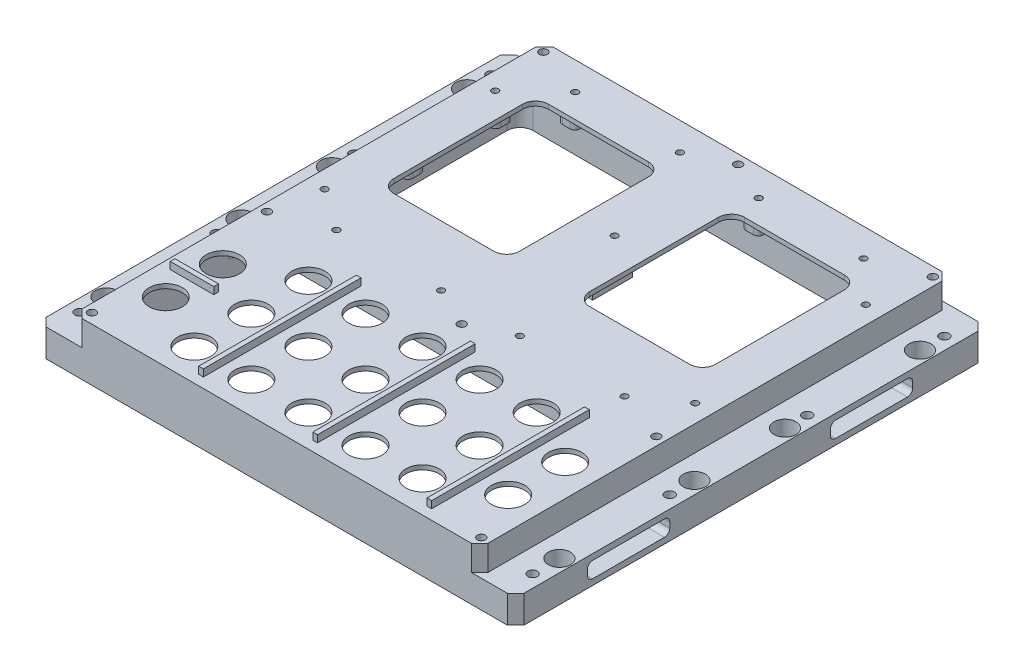
SolidWorks part; units mm, degrees
ref_plane "Front Plane" through (0, 0, 0) normal (0, 0, 1) x (1, 0, 0)
ref_plane "Top Plane" through (0, 0, 0) normal (0, 1, 0) x (1, 0, 0)
ref_plane "Right Plane" through (0, 0, 0) normal (1, 0, 0) x (0, 0, -1)
sketch "Sketch1" plane through (0, 0, 0) normal (0, 1, 0) x (1, 0, 0)
  line L0 (0, 199.644) -> (3.556, 203.2)
  line L1 (3.556, 0) -> (202.7936, 0)
  line L2 (0, 3.556) -> (0, 199.644)
  line L3 (3.556, 203.2) -> (202.7936, 203.2)
  line L4 (206.3496, 3.556) -> (206.3496, 199.644)
  line L5 (202.7936, 203.2) -> (206.3496, 199.644)
  line L6 (202.7936, 0) -> (206.3496, 3.556)
  line L7 (0, 3.556) -> (3.556, 0)
  point P0 (0, 0)
  point P1 (206.3496, 203.2)
  point P2 (0, 203.2)
  point P3 (206.3496, 0)
  dimension "D1" = 203.2
  dimension "D2" = 206.3496
  dimension "D3" = 3.556
  dimension "D4" = 45
  dimension "D5" = 3.556
  dimension "D6" = 45
  dimension "D7" = 3.556
  dimension "D8" = 45
  dimension "D9" = 3.556
  dimension "D10" = 45
extrude "Boss-Extrude1" add sketch "Sketch1" along normal blind 22.8727
sketch "Sketch3" plane through (0, 0, -203.2) normal (0, 0, -1) x (-1, 0, 0)
  line L0 (-190.8048, 11.9507) -> (-15.5448, 11.9507) construction
  line L1 (-206.3496, 22.8727) -> (-190.8048, 22.8727)
  line L2 (-206.3496, 22.8727) -> (-206.3496, 11.9507)
  line L3 (-206.3496, 11.9507) -> (-190.8048, 11.9507)
  line L4 (-190.8048, 22.8727) -> (-190.8048, 11.9507)
  line L5 (0, 22.8727) -> (-15.5448, 22.8727)
  line L6 (0, 22.8727) -> (0, 11.9507)
  line L7 (0, 11.9507) -> (-15.5448, 11.9507)
  line L8 (-15.5448, 22.8727) -> (-15.5448, 11.9507)
  line L9 (-202.7936, 22.8727) -> (-3.556, 22.8727) construction
  point P10 (-103.1748, 11.9507)
  point P13 (-103.1748, 22.8727)
  dimension "D1" = 10.922
  dimension "D2" = 175.26
extrude "Cut-Extrude1" cut sketch "Sketch3" against normal through all
chamfer "Chamfer1" distance 3.556 angle 45 4 edges at (190.8048, 17.4117, 0) (15.5448, 17.4117, 0) (15.5448, 17.4117, -203.2) (190.8048, 17.4117, -203.2)
sketch "Sketch4" plane through (0, 22.8727, 0) normal (0, 1, 0) x (1, 0, 0)
  line L0 (-41.9282, 73.533) -> (82.8548, 73.533)
  line L1 (190.8048, 3.556) -> (190.8048, 199.644) construction
  line L2 (19.1008, 0) -> (187.2488, 0) construction
  line L3 (39.6748, 180.848) -> (82.8548, 180.848)
  line L4 (34.0868, 175.26) -> (34.0868, 119.634)
  line L5 (39.6748, 114.046) -> (82.8548, 114.046)
  line L6 (88.4428, 175.26) -> (88.4428, 119.634)
  line L7 (124.2568, 180.848) -> (167.4368, 180.848)
  line L8 (118.6688, 175.26) -> (118.6688, 119.634)
  line L9 (124.2568, 114.046) -> (167.4368, 114.046)
  line L10 (173.0248, 175.26) -> (173.0248, 119.634)
  line L12 (187.2234, 11.7526) -> (187.2234, -12.2812) construction
  arc A0 (124.2568, 180.848) -> (118.6688, 175.26) centre (124.2568, 175.26) ccw
  arc A1 (167.4368, 180.848) -> (173.0248, 175.26) centre (167.4368, 175.26) cw
  arc A2 (167.4368, 114.046) -> (173.0248, 119.634) centre (167.4368, 119.634) ccw
  arc A3 (118.6688, 119.634) -> (124.2568, 114.046) centre (124.2568, 119.634) ccw
  arc A4 (82.8548, 114.046) -> (88.4428, 119.634) centre (82.8548, 119.634) ccw
  arc A5 (34.0868, 119.634) -> (39.6748, 114.046) centre (39.6748, 119.634) ccw
  arc A6 (39.6748, 180.848) -> (34.0868, 175.26) centre (39.6748, 175.26) ccw
  arc A7 (82.8548, 180.848) -> (88.4428, 175.26) centre (82.8548, 175.26) cw
  circle A8 centre (29.2354, 26.035) radius 7.1819
  circle A9 centre (177.0634, 26.035) radius 7.1819
  circle A10 centre (177.0634, 50.673) radius 7.1819
  circle A11 centre (29.2354, 50.673) radius 7.1819
  circle A12 centre (53.8734, 62.992) radius 7.1819
  circle A13 centre (53.8734, 38.354) radius 7.1819
  circle A14 centre (53.8734, 13.716) radius 7.1819
  circle A15 centre (78.5114, 13.716) radius 7.1819
  circle A16 centre (78.5114, 38.354) radius 7.1819
  circle A17 centre (78.5114, 62.992) radius 7.1819
  circle A18 centre (103.1494, 62.992) radius 7.1819
  circle A19 centre (127.7874, 62.992) radius 7.1819
  circle A20 centre (152.4254, 62.992) radius 7.1819
  circle A21 centre (103.1494, 38.354) radius 7.1819
  circle A22 centre (127.7874, 38.354) radius 7.1819
  circle A23 centre (152.4254, 38.354) radius 7.1819
  circle A24 centre (103.1494, 13.716) radius 7.1819
  circle A25 centre (127.7874, 13.716) radius 7.1819
  circle A26 centre (152.4254, 13.716) radius 7.1819
  point P26 (34.0868, 114.046)
  point P29 (34.0868, 180.848)
  point P32 (88.4428, 180.848)
  dimension "D5" = 5.588
  dimension "D6" = 5.588
  dimension "D9" = 14.3637
  dimension "D12" = 59.436
  dimension "D1" = 3.5814
  dimension "D2" = 66.802
  dimension "D3" = 54.356
  dimension "D4" = 180.848
  dimension "D7" = 17.78
  dimension "D8" = 102.362
  dimension "D10" = 10.16
  dimension "D11" = 34.798
  dimension "D13" = 84.074
  dimension "D14" = 108.712
  dimension "D15" = 133.35
  dimension "D16" = 157.988
  dimension "D17" = 73.533
  dimension "D18" = 10.541
  dimension "D19" = 35.179
  dimension "D20" = 59.817
  dimension "D21" = 22.86
  dimension "D22" = 47.498
extrude "Cut-Extrude2" cut sketch "Sketch4" against normal through all contours A7 L3 A6 L4 A5 L5 A4 L6 | L8 A3 L9 A2 L10 A1 L7 A0 | A19 | A18 | A13 | A14 | A17 | A12 | A11 | A8 | A16 | A21 | A22 | A20 | A10 | A9 | A23 | A26 | A25 | A24 | A15
sketch "Sketch5" plane through (0, 22.8727, 0) normal (0, 1, 0) x (1, 0, 0)
  line L0 (190.8048, 3.556) -> (190.8048, 199.644) construction
  line L1 (19.8628, 39.37) -> (38.6588, 39.37)
  line L2 (19.8628, 39.37) -> (19.8628, 37.338)
  line L3 (19.8628, 37.338) -> (38.6588, 37.338)
  line L4 (38.6588, 39.37) -> (38.6588, 37.338)
  line L5 (65.1764, 72.39) -> (67.2084, 72.39)
  line L6 (65.1764, 72.39) -> (65.1764, 4.318)
  line L7 (65.1764, 4.318) -> (67.2084, 4.318)
  line L8 (67.2084, 72.39) -> (67.2084, 4.318)
  line L9 (114.4524, 72.39) -> (116.4844, 72.39)
  line L10 (114.4524, 72.39) -> (114.4524, 4.318)
  line L11 (114.4524, 4.318) -> (116.4844, 4.318)
  line L12 (116.4844, 72.39) -> (116.4844, 4.318)
  line L13 (165.7604, 72.39) -> (163.7284, 72.39)
  line L14 (165.7604, 72.39) -> (165.7604, 4.318)
  line L15 (165.7604, 4.318) -> (163.7284, 4.318)
  line L16 (163.7284, 72.39) -> (163.7284, 4.318)
  line L17 (19.1008, 0) -> (187.2488, 0) construction
  circle A0 centre (53.8734, 13.716) radius 7.1819 construction
  circle A1 centre (78.5114, 13.716) radius 7.1819 construction
  circle A2 centre (103.1494, 13.716) radius 7.1819 construction
  circle A4 centre (152.4254, 13.716) radius 7.1819 construction
  circle A5 centre (29.2354, 50.673) radius 7.1819 construction
  circle A6 centre (29.2354, 26.035) radius 7.1819 construction
  dimension "D1" = 11.303
  dimension "D2" = 11.303
  dimension "D4" = 11.303
  dimension "D6" = 11.303
  dimension "D3" = 11.303
  dimension "D5" = 68.072
  dimension "D7" = 11.303
  dimension "D8" = 152.146
  dimension "D9" = 18.796
  dimension "D10" = 4.318
extrude "Boss-Extrude2" add sketch "Sketch5" along normal blind 3.048
sketch "Sketch6" plane through (0, 0, -203.2) normal (0, 0, -1) x (-1, 0, 0)
  line L0 (-133.7056, 20.3327) -> (-109.5756, 20.3327)
  line L1 (-174.5996, 20.3327) -> (-146.4056, 20.3327)
  line L2 (-176.8856, 18.0467) -> (-176.8856, 4.826)
  line L3 (-174.5996, 2.54) -> (-146.4056, 2.54)
  line L4 (-144.1196, 18.0467) -> (-144.1196, 4.826)
  line L5 (-96.8756, 20.3327) -> (-72.7456, 20.3327)
  line L6 (-99.1616, 18.0467) -> (-99.1616, 4.826)
  line L7 (-96.8756, 2.54) -> (-72.7456, 2.54)
  line L8 (-70.4596, 18.0467) -> (-70.4596, 4.826)
  line L9 (-59.7916, 20.3327) -> (-31.5976, 20.3327)
  line L10 (-62.0776, 18.0467) -> (-62.0776, 4.826)
  line L11 (-59.7916, 2.54) -> (-31.5976, 2.54)
  line L12 (-29.3116, 18.0467) -> (-29.3116, 4.826)
  line L13 (-135.9916, 18.0467) -> (-135.9916, 4.826)
  line L14 (-133.7056, 2.54) -> (-109.5756, 2.54)
  line L15 (-107.2896, 18.0467) -> (-107.2896, 4.826)
  line L16 (-206.3496, 11.9507) -> (-206.3496, 0) construction
  line L17 (-187.2488, 22.8727) -> (-19.1008, 22.8727) construction
  line L18 (-202.7936, 0) -> (-3.556, 0) construction
  arc A0 (-31.5976, 2.54) -> (-29.3116, 4.826) centre (-31.5976, 4.826) ccw
  arc A1 (-31.5976, 20.3327) -> (-29.3116, 18.0467) centre (-31.5976, 18.0467) cw
  arc A2 (-59.7916, 20.3327) -> (-62.0776, 18.0467) centre (-59.7916, 18.0467) ccw
  arc A3 (-62.0776, 4.826) -> (-59.7916, 2.54) centre (-59.7916, 4.826) ccw
  arc A4 (-72.7456, 2.54) -> (-70.4596, 4.826) centre (-72.7456, 4.826) ccw
  arc A5 (-72.7456, 20.3327) -> (-70.4596, 18.0467) centre (-72.7456, 18.0467) cw
  arc A6 (-99.1616, 4.826) -> (-96.8756, 2.54) centre (-96.8756, 4.826) ccw
  arc A7 (-96.8756, 20.3327) -> (-99.1616, 18.0467) centre (-96.8756, 18.0467) ccw
  arc A8 (-146.4056, 20.3327) -> (-144.1196, 18.0467) centre (-146.4056, 18.0467) cw
  arc A9 (-146.4056, 2.54) -> (-144.1196, 4.826) centre (-146.4056, 4.826) ccw
  arc A10 (-176.8856, 4.826) -> (-174.5996, 2.54) centre (-174.5996, 4.826) ccw
  arc A11 (-174.5996, 20.3327) -> (-176.8856, 18.0467) centre (-174.5996, 18.0467) ccw
  arc A12 (-109.5756, 2.54) -> (-107.2896, 4.826) centre (-109.5756, 4.826) ccw
  arc A13 (-109.5756, 20.3327) -> (-107.2896, 18.0467) centre (-109.5756, 18.0467) cw
  arc A14 (-135.9916, 4.826) -> (-133.7056, 2.54) centre (-133.7056, 4.826) ccw
  arc A15 (-133.7056, 20.3327) -> (-135.9916, 18.0467) centre (-133.7056, 18.0467) ccw
  dimension "D1" = 2.286
  dimension "D10" = 2.286
  dimension "D2" = 32.766
  dimension "D3" = 28.702
  dimension "D4" = 29.464
  dimension "D5" = 70.358
  dimension "D6" = 2.54
  dimension "D7" = 2.54
  dimension "D8" = 107.188
  dimension "D9" = 144.272
extrude "Cut-Extrude3" cut sketch "Sketch6" against normal blind 7.874
fillet "Fillet1" radius 2.286 32 edges at (61.408, 3.2096, -195.326) (62.0776, 11.4363, -195.326) (61.408, 19.6631, -195.326) (45.6946, 20.3327, -195.326) (29.9812, 19.6631, -195.326) (29.3116, 11.4364, -195.326) (29.9812, 3.2096, -195.326) (98.492, 3.2096, -195.326) (99.1616, 11.4363, -195.326) (98.492, 19.6631, -195.326) (84.8106, 20.3327, -195.326) (71.1292, 19.6631, -195.326) (70.4596, 11.4364, -195.326) (71.1292, 3.2096, -195.326) (135.322, 3.2096, -195.326) (135.9916, 11.4363, -195.326) (135.322, 19.6631, -195.326) (121.6406, 20.3327, -195.326) (107.9592, 19.6631, -195.326) (107.2896, 11.4363, -195.326) (107.9592, 3.2096, -195.326) (176.216, 3.2096, -195.326) (176.8856, 11.4363, -195.326) (176.216, 19.6631, -195.326) (160.5026, 20.3327, -195.326) (144.7892, 19.6631, -195.326) (144.1196, 11.4363, -195.326) (144.7892, 3.2096, -195.326) (45.6946, 2.54, -195.326) (84.8106, 2.54, -195.326) (121.6406, 2.54, -195.326) (160.5026, 2.54, -195.326)
sketch "Sketch7" plane through (206.3496, 0, 0) normal (1, 0, 0) x (0, 0, -1)
  line L0 (3.556, 11.9507) -> (199.644, 11.9507) construction
  line L1 (33.274, 2.54) -> (64.262, 2.54)
  line L2 (30.988, 4.826) -> (30.988, 7.1247)
  line L3 (33.274, 9.4107) -> (64.262, 9.4107)
  line L4 (66.548, 4.826) -> (66.548, 7.1247)
  line L5 (138.176, 2.54) -> (169.164, 2.54)
  line L6 (135.89, 4.826) -> (135.89, 7.1247)
  line L7 (138.176, 9.4107) -> (169.164, 9.4107)
  line L8 (171.45, 4.826) -> (171.45, 7.1247)
  line L9 (3.556, 0) -> (199.644, 0) construction
  arc A0 (169.164, 2.54) -> (171.45, 4.826) centre (169.164, 4.826) ccw
  arc A1 (169.164, 9.4107) -> (171.45, 7.1247) centre (169.164, 7.1247) cw
  arc A2 (138.176, 2.54) -> (135.89, 4.826) centre (138.176, 4.826) cw
  arc A3 (135.89, 7.1247) -> (138.176, 9.4107) centre (138.176, 7.1247) cw
  arc A4 (64.262, 2.54) -> (66.548, 4.826) centre (64.262, 4.826) ccw
  arc A5 (64.262, 9.4107) -> (66.548, 7.1247) centre (64.262, 7.1247) cw
  arc A6 (30.988, 7.1247) -> (33.274, 9.4107) centre (33.274, 7.1247) cw
  arc A7 (33.274, 2.54) -> (30.988, 4.826) centre (33.274, 4.826) cw
  dimension "D1" = 2.286
  dimension "D2" = 35.56
  dimension "D3" = 2.54
  dimension "D4" = 2.54
  dimension "D5" = 30.988
  dimension "D6" = 135.89
extrude "Cut-Extrude4" cut sketch "Sketch7" against normal blind 12.7
ref_plane "Plane1" through (103.1748, 0, 0) normal (1, 0, 0) x (0, 0, -1)
mirror "Mirror1" about plane through (103.1748, 0, 0) normal (1, 0, 0) of "Cut-Extrude4"
sketch "Sketch8" plane through (0, 0, 0) normal (0, -1, 0) x (1, 0, 0)
  line L0 (39.37, -2.54) -> (50.4656, -2.54)
  line L3 (188.5696, -18.6857) -> (188.5696, -64.6263)
  line L10 (178.5916, -74.676) -> (27.758, -74.676)
  line L13 (17.78, -64.6263) -> (17.78, -18.6857)
  line L16 (3.556, 0) -> (202.7936, 0) construction
  line L17 (206.3496, -3.556) -> (206.3496, -199.644) construction
  line L19 (141.7846, -8.89) -> (138.4282, -8.89)
  line L22 (64.5142, -8.89) -> (67.8706, -8.89)
  line L24 (81.9192, -2.54) -> (99.7416, -2.54)
  line L25 (155.8332, -2.54) -> (166.9796, -2.54)
  line L26 (106.5572, -2.54) -> (124.3796, -2.54)
  arc A0 (188.5696, -64.6263) -> (184.0865, -70.104) centre (182.9816, -64.6263) cw
  arc A1 (184.0865, -70.104) -> (178.5916, -74.676) centre (178.5916, -69.088) cw
  arc A2 (27.758, -74.676) -> (22.2631, -70.104) centre (27.758, -69.088) cw
  arc A3 (22.2631, -70.104) -> (17.78, -64.6263) centre (23.368, -64.6263) cw
  arc A4 (184.0865, -13.208) -> (188.5696, -18.6857) centre (182.9816, -18.6857) cw
  arc A5 (17.78, -18.6857) -> (22.2631, -13.208) centre (23.368, -18.6857) cw
  arc A6 (184.0865, -13.208) -> (166.9796, -2.54) centre (166.9796, -21.59) ccw
  arc A8 (39.37, -2.54) -> (22.2631, -13.208) centre (39.37, -21.59) ccw
  arc A9 (50.4656, -2.54) -> (64.5142, -8.89) centre (53.8734, -13.716) cw
  circle A10 centre (53.8734, -13.716) radius 7.1819 construction
  arc A11 (81.9192, -2.54) -> (67.8706, -8.89) centre (78.5114, -13.716) ccw
  arc A12 (106.5572, -2.54) -> (99.7416, -2.54) centre (103.1494, -13.716) ccw
  arc A13 (138.4282, -8.89) -> (124.3796, -2.54) centre (127.7874, -13.716) ccw
  arc A14 (141.7846, -8.89) -> (155.8332, -2.54) centre (152.4254, -13.716) cw
  point P18 (0, 0)
  point P20 (0, 0)
  point P23 (0, 0)
  point P30 (0, 0)
  point P49 (0, 0)
  point P50 (0, 0)
  dimension "D1" = 5.588
  dimension "D2" = 5.588
  dimension "D7" = 19.05
  dimension "D8" = 19.05
  dimension "D14" = 11.684
  dimension "D15" = 11.684
  dimension "D16" = 11.684
  dimension "D17" = 11.684
  dimension "D18" = 11.684
  dimension "D3" = 2.54
  dimension "D4" = 188.5696
  dimension "D5" = 17.78
  dimension "D6" = 13.208
  dimension "D9" = 21.59
  dimension "D10" = 21.59
  dimension "D11" = 74.676
  dimension "D12" = 4.572
  dimension "D13" = 8.89
extrude "Cut-Extrude5" cut sketch "Sketch8" against normal offset from surface (20.9677 mm away) 1.905 up to face at (115.4684, 22.8727, -38.354)
sketch "Sketch9" plane through (0, 11.9507, 0) normal (0, 1, 0) x (1, 0, 0)
  line L1 (5.3848, 4.318) -> (200.9648, 4.318) construction
  line L2 (19.1008, 0) -> (187.2488, 0) construction
  line L3 (15.5448, 3.556) -> (15.5448, 199.644) construction
  line L6 (202.7936, 0) -> (187.2488, 0) construction
  point P0 (5.3848, 179.959)
  point P1 (5.3848, 121.666)
  point P2 (5.3848, 82.55)
  point P3 (5.3848, 24.257)
  point P4 (200.9648, 24.257)
  point P5 (200.9648, 82.55)
  point P6 (200.9648, 121.666)
  point P7 (200.9648, 179.959)
  point P8 (200.9648, 71.882)
  point P9 (5.3848, 12.7)
  point P11 (200.9648, 131.318)
  point P18 (200.9648, 190.5)
  point P19 (5.3848, 4.318)
  point P20 (5.3848, 190.5)
  point P21 (5.3848, 131.318)
  point P23 (5.3848, 71.882)
  point P28 (200.9648, 12.7)
  dimension "D1" = 19.939
  dimension "D2" = 78.232
  dimension "D3" = 117.348
  dimension "D4" = 175.641
  dimension "D5" = 195.58
  dimension "D6" = 4.318
  dimension "D7" = 10.16
  dimension "D8" = 12.7
  dimension "D9" = 59.182
  dimension "D10" = 118.618
  dimension "D11" = 177.8
hole_wizard "Hole1" positions "Sketch10" profile "Sketch11" legacy end condition through all
sketch "Sketch10" plane through (0, 11.9507, 0) normal (0, 1, 0) x (1, 0, 0)
  point P0 (5.3848, 82.55)
  point P3 (5.3848, 121.666)
  point P6 (5.3848, 179.959)
  point P9 (5.3848, 24.257)
  point P12 (200.9648, 24.257)
  point P15 (200.9648, 82.55)
  point P18 (200.9648, 121.666)
  point P24 (200.9648, 179.959)
sketch "Sketch11" plane through (5.3848, 11.9507, -82.55) normal (1, 0, 0) x (0, 0, 1)
  line L0 (0, 0) -> (0, 13.1793)
  line L1 (0, 13.1793) -> (2.0447, 11.9507)
  line L2 (2.0447, 11.9507) -> (2.0447, 9.652)
  line L3 (2.0447, 9.652) -> (4.7625, 9.652)
  line L4 (4.7625, 0) -> (0, 0)
  line L5 (0, -11.3109) -> (0, 121.1557) construction
  line L6 (0, 13.1793) -> (-2.0447, 11.9507) construction
  line L7 (4.7625, 9.652) -> (4.7625, 0)
  dimension "Depth" = 11.9507
  dimension "Drill Angle" = 118
  dimension "Diameter" = 4.0894
  dimension "C-Bore Diameter" = 9.525
  dimension "C-Bore Depth" = 9.652
hole_wizard "Hole2" positions "Sketch14" profile "Sketch15" legacy end condition through all
sketch "Sketch14" plane through (0, 11.9507, 0) normal (0, 1, 0) x (1, 0, 0)
  point P0 (5.3848, 190.5)
  point P3 (5.3848, 131.318)
  point P6 (5.3848, 71.882)
  point P9 (5.3848, 12.7)
  point P12 (200.9648, 12.7)
  point P15 (200.9648, 71.882)
  point P18 (200.9648, 131.318)
  point P21 (200.9648, 190.5)
sketch "Sketch15" plane through (5.3848, 11.9507, -190.5) normal (1, 0, 0) x (0, 0, 1)
  line L0 (0, 0) -> (0, 11.9507)
  line L1 (0, 11.9507) -> (2.0447, 11.9507)
  line L2 (2.0447, 11.9507) -> (2.0447, 0)
  line L3 (2.0447, 0) -> (0, 0)
  line L4 (0, 110) -> (0, -10) construction
  dimension "Diameter" = 4.0894
  dimension "Depth" = 11.9507
sketch "Sketch16" plane through (0, 22.8727, 0) normal (0, 1, 0) x (1, 0, 0)
  line L0 (5.3848, 4.318) -> (200.9648, 4.318) construction
  line L1 (19.1008, 0) -> (187.2488, 0) construction
  circle A0 centre (177.0634, 26.035) radius 7.1819 construction
  point P0 (19.0754, 4.318)
  point P1 (187.2234, 4.318)
  point P4 (187.2234, 79.883)
  point P5 (103.1494, 79.883)
  point P6 (19.0754, 79.883)
  point P7 (19.0754, 199.263)
  point P8 (103.1494, 199.263)
  point P9 (187.2234, 199.263)
  dimension "D2" = 10.16
  dimension "D1" = 168.148
  dimension "D3" = 84.074
  dimension "D4" = 199.263
  dimension "D5" = 79.883
hole_wizard "Hole3" positions "Sketch17" profile "Sketch18" legacy
sketch "Sketch17" plane through (0, 22.8727, 0) normal (0, 1, 0) x (1, 0, 0)
  point P0 (19.0754, 199.263)
  point P3 (19.0754, 79.883)
  point P6 (19.0754, 4.318)
  point P9 (103.1494, 79.883)
  point P12 (187.2234, 79.883)
  point P15 (187.2234, 4.318)
  point P18 (187.2234, 199.263)
  point P21 (103.1494, 199.263)
sketch "Sketch18" plane through (19.0754, 22.8727, -199.263) normal (1, 0, 0) x (0, 0, 1)
  line L0 (0, 0) -> (0, 7.62)
  line L1 (0, 7.62) -> (1.7526, 7.62)
  line L2 (1.7526, 7.62) -> (1.7526, 0)
  line L3 (1.7526, 0) -> (0, 0)
  line L4 (0, 110) -> (0, -10) construction
  dimension "Diameter" = 3.5052
  dimension "Depth" = 7.62
sketch "Sketch19" plane through (0, 0, 0) normal (0, -1, 0) x (1, 0, 0)
  line L0 (31.5396, -190.5) -> (37.1856, -190.5)
  line L1 (37.1856, -190.5) -> (37.1856, -189.484)
  line L2 (39.4716, -187.198) -> (42.5196, -187.198)
  line L3 (44.8056, -189.484) -> (44.8056, -190.5)
  line L4 (44.8056, -190.5) -> (82.3976, -190.5)
  line L5 (82.3976, -190.5) -> (82.3976, -189.484)
  line L6 (84.6836, -187.198) -> (87.7316, -187.198)
  line L7 (90.0176, -189.484) -> (90.0176, -190.5)
  line L8 (90.0176, -190.5) -> (116.4336, -190.5)
  line L9 (116.4336, -190.5) -> (116.4336, -189.484)
  line L10 (118.7196, -187.198) -> (121.7676, -187.198)
  line L11 (124.0536, -189.484) -> (124.0536, -190.5)
  line L12 (124.0536, -190.5) -> (161.6456, -190.5)
  line L13 (161.6456, -190.5) -> (161.6456, -189.484)
  line L14 (163.9316, -187.198) -> (166.9796, -187.198)
  line L15 (169.2656, -189.484) -> (169.2656, -190.5)
  line L16 (169.2656, -190.5) -> (182.9816, -190.5)
  line L17 (188.5696, -184.912) -> (188.5696, -180.467)
  line L18 (186.2836, -178.181) -> (181.4576, -178.181)
  line L19 (179.1716, -175.895) -> (179.1716, -172.847)
  line L20 (181.4576, -170.561) -> (186.2836, -170.561)
  line L21 (188.5696, -168.275) -> (188.5696, -120.65)
  line L22 (186.2836, -118.364) -> (181.4576, -118.364)
  line L23 (179.1716, -116.078) -> (179.1716, -99.06)
  line L24 (181.4576, -96.774) -> (186.2836, -96.774)
  line L25 (188.5696, -94.488) -> (188.5696, -86.614)
  line L26 (186.2836, -84.328) -> (181.4576, -84.328)
  line L27 (179.1716, -82.042) -> (179.1716, -80.264)
  line L28 (176.8856, -77.978) -> (171.5516, -77.978)
  line L29 (169.2656, -80.264) -> (169.2656, -89.408)
  line L30 (166.9796, -91.694) -> (163.9316, -91.694)
  line L31 (161.6456, -89.408) -> (161.6456, -80.264)
  line L32 (159.3596, -77.978) -> (126.3396, -77.978)
  line L33 (124.0536, -80.264) -> (124.0536, -89.408)
  line L34 (121.7676, -91.694) -> (118.7196, -91.694)
  line L35 (116.4336, -89.408) -> (116.4336, -80.264)
  line L36 (114.1476, -77.978) -> (109.3216, -77.978)
  line L37 (107.0356, -80.264) -> (107.0356, -82.042)
  line L38 (104.7496, -84.328) -> (101.7016, -84.328)
  line L39 (99.4156, -82.042) -> (99.4156, -80.264)
  line L40 (97.1296, -77.978) -> (92.3036, -77.978)
  line L41 (90.0176, -80.264) -> (90.0176, -89.408)
  line L42 (87.7316, -91.694) -> (84.6836, -91.694)
  line L43 (82.3976, -89.408) -> (82.3976, -80.264)
  line L44 (80.1116, -77.978) -> (47.0916, -77.978)
  line L45 (44.8056, -80.264) -> (44.8056, -89.408)
  line L46 (42.5196, -91.694) -> (39.4716, -91.694)
  line L47 (37.1856, -89.408) -> (37.1856, -80.264)
  line L48 (34.8996, -77.978) -> (29.464, -77.978)
  line L49 (27.178, -80.264) -> (27.178, -82.042)
  line L50 (24.892, -84.328) -> (20.066, -84.328)
  line L51 (17.78, -86.614) -> (17.78, -94.488)
  line L52 (20.066, -96.774) -> (24.892, -96.774)
  line L53 (27.178, -99.06) -> (27.178, -116.078)
  line L54 (24.892, -118.364) -> (20.066, -118.364)
  line L55 (17.78, -120.65) -> (17.78, -130.302)
  line L56 (20.066, -132.588) -> (24.892, -132.588)
  line L57 (27.178, -134.874) -> (27.178, -137.922)
  line L58 (24.892, -140.208) -> (20.066, -140.208)
  line L59 (17.78, -142.494) -> (17.78, -168.275)
  line L60 (20.066, -170.561) -> (24.892, -170.561)
  line L61 (27.178, -172.847) -> (27.178, -175.895)
  line L62 (24.892, -178.181) -> (20.066, -178.181)
  line L63 (17.78, -180.467) -> (17.78, -184.912)
  line L64 (23.368, -190.5) -> (31.5396, -190.5)
  line L65 (206.3496, -3.556) -> (206.3496, -199.644) construction
  line L66 (200.9648, -190.5) -> (191.9073, -190.5) construction
  line L67 (3.556, 0) -> (202.7936, 0) construction
  line L68 (27.758, -74.676) -> (178.5916, -74.676) construction
  line L70 (99.4156, -132.588) -> (107.0356, -132.588)
  line L71 (99.4156, -132.588) -> (99.4156, -149.86)
  line L72 (99.4156, -149.86) -> (107.0356, -149.86)
  line L73 (107.0356, -132.588) -> (107.0356, -149.86)
  line L74 (72.4916, -100.838) -> (80.1116, -100.838)
  line L75 (72.4916, -100.838) -> (72.4916, -108.458)
  line L76 (72.4916, -108.458) -> (80.1116, -108.458)
  line L77 (80.1116, -100.838) -> (80.1116, -108.458)
  line L78 (126.5936, -100.838) -> (134.2136, -100.838)
  line L79 (126.5936, -100.838) -> (126.5936, -108.458)
  line L80 (126.5936, -108.458) -> (134.2136, -108.458)
  line L81 (134.2136, -100.838) -> (134.2136, -108.458)
  arc A0 (179.1716, -99.06) -> (181.4576, -96.774) centre (181.4576, -99.06) cw
  arc A1 (181.4576, -118.364) -> (179.1716, -116.078) centre (181.4576, -116.078) cw
  arc A2 (179.1716, -172.847) -> (181.4576, -170.561) centre (181.4576, -172.847) cw
  arc A3 (181.4576, -178.181) -> (179.1716, -175.895) centre (181.4576, -175.895) cw
  arc A4 (37.1856, -189.484) -> (39.4716, -187.198) centre (39.4716, -189.484) cw
  arc A5 (42.5196, -187.198) -> (44.8056, -189.484) centre (42.5196, -189.484) cw
  arc A6 (82.3976, -189.484) -> (84.6836, -187.198) centre (84.6836, -189.484) cw
  arc A7 (87.7316, -187.198) -> (90.0176, -189.484) centre (87.7316, -189.484) cw
  arc A8 (116.4336, -189.484) -> (118.7196, -187.198) centre (118.7196, -189.484) cw
  arc A9 (121.7676, -187.198) -> (124.0536, -189.484) centre (121.7676, -189.484) cw
  arc A10 (161.6456, -189.484) -> (163.9316, -187.198) centre (163.9316, -189.484) cw
  arc A11 (166.9796, -187.198) -> (169.2656, -189.484) centre (166.9796, -189.484) cw
  arc A12 (39.4716, -91.694) -> (37.1856, -89.408) centre (39.4716, -89.408) cw
  arc A13 (44.8056, -89.408) -> (42.5196, -91.694) centre (42.5196, -89.408) cw
  arc A14 (84.6836, -91.694) -> (82.3976, -89.408) centre (84.6836, -89.408) cw
  arc A15 (90.0176, -89.408) -> (87.7316, -91.694) centre (87.7316, -89.408) cw
  arc A16 (101.7016, -84.328) -> (99.4156, -82.042) centre (101.7016, -82.042) cw
  arc A17 (107.0356, -82.042) -> (104.7496, -84.328) centre (104.7496, -82.042) cw
  arc A18 (118.7196, -91.694) -> (116.4336, -89.408) centre (118.7196, -89.408) cw
  arc A19 (124.0536, -89.408) -> (121.7676, -91.694) centre (121.7676, -89.408) cw
  arc A20 (163.9316, -91.694) -> (161.6456, -89.408) centre (163.9316, -89.408) cw
  arc A21 (169.2656, -89.408) -> (166.9796, -91.694) centre (166.9796, -89.408) cw
  arc A22 (29.464, -77.978) -> (27.178, -80.264) centre (29.464, -80.264) ccw
  arc A23 (37.1856, -80.264) -> (34.8996, -77.978) centre (34.8996, -80.264) ccw
  arc A24 (47.0916, -77.978) -> (44.8056, -80.264) centre (47.0916, -80.264) ccw
  arc A25 (82.3976, -80.264) -> (80.1116, -77.978) centre (80.1116, -80.264) ccw
  arc A26 (92.3036, -77.978) -> (90.0176, -80.264) centre (92.3036, -80.264) ccw
  arc A27 (99.4156, -80.264) -> (97.1296, -77.978) centre (97.1296, -80.264) ccw
  arc A28 (109.3216, -77.978) -> (107.0356, -80.264) centre (109.3216, -80.264) ccw
  arc A29 (116.4336, -80.264) -> (114.1476, -77.978) centre (114.1476, -80.264) ccw
  arc A30 (126.3396, -77.978) -> (124.0536, -80.264) centre (126.3396, -80.264) ccw
  arc A31 (161.6456, -80.264) -> (159.3596, -77.978) centre (159.3596, -80.264) ccw
  arc A32 (171.5516, -77.978) -> (169.2656, -80.264) centre (171.5516, -80.264) ccw
  arc A33 (179.1716, -80.264) -> (176.8856, -77.978) centre (176.8856, -80.264) ccw
  arc A34 (181.4576, -84.328) -> (179.1716, -82.042) centre (181.4576, -82.042) cw
  arc A35 (188.5696, -86.614) -> (186.2836, -84.328) centre (186.2836, -86.614) ccw
  arc A36 (186.2836, -96.774) -> (188.5696, -94.488) centre (186.2836, -94.488) ccw
  arc A37 (188.5696, -120.65) -> (186.2836, -118.364) centre (186.2836, -120.65) ccw
  arc A38 (20.066, -178.181) -> (17.78, -180.467) centre (20.066, -180.467) ccw
  arc A39 (17.78, -168.275) -> (20.066, -170.561) centre (20.066, -168.275) ccw
  arc A40 (20.066, -140.208) -> (17.78, -142.494) centre (20.066, -142.494) ccw
  arc A41 (17.78, -130.302) -> (20.066, -132.588) centre (20.066, -130.302) ccw
  arc A42 (20.066, -118.364) -> (17.78, -120.65) centre (20.066, -120.65) ccw
  arc A43 (17.78, -94.488) -> (20.066, -96.774) centre (20.066, -94.488) ccw
  arc A44 (20.066, -84.328) -> (17.78, -86.614) centre (20.066, -86.614) ccw
  arc A45 (27.178, -82.042) -> (24.892, -84.328) centre (24.892, -82.042) cw
  arc A46 (24.892, -96.774) -> (27.178, -99.06) centre (24.892, -99.06) cw
  arc A47 (27.178, -116.078) -> (24.892, -118.364) centre (24.892, -116.078) cw
  arc A48 (24.892, -132.588) -> (27.178, -134.874) centre (24.892, -134.874) cw
  arc A49 (27.178, -137.922) -> (24.892, -140.208) centre (24.892, -137.922) cw
  arc A50 (27.178, -175.895) -> (24.892, -178.181) centre (24.892, -175.895) cw
  arc A51 (24.892, -170.561) -> (27.178, -172.847) centre (24.892, -172.847) cw
  arc A52 (188.5696, -180.467) -> (186.2836, -178.181) centre (186.2836, -180.467) ccw
  arc A53 (186.2836, -170.561) -> (188.5696, -168.275) centre (186.2836, -168.275) ccw
  arc A54 (17.78, -184.912) -> (23.368, -190.5) centre (23.368, -184.912) ccw
  arc A55 (182.9816, -190.5) -> (188.5696, -184.912) centre (182.9816, -184.912) ccw
  point P68 (63.6016, -190.5)
  point P71 (40.9956, -187.198)
  point P79 (179.1716, -96.774)
  point P82 (179.1716, -118.364)
  point P101 (161.6456, -187.198)
  point P104 (169.2656, -187.198)
  point P117 (107.0356, -84.328)
  point P180 (27.178, -132.588)
  point P183 (27.178, -140.208)
  point P186 (27.178, -178.181)
  point P189 (27.178, -170.561)
  point P209 (0, 0)
  point P210 (0, 0)
  point P211 (0, 0)
  point P212 (0, 0)
  dimension "D21" = 2.286
  dimension "D22" = 2.286
  dimension "D23" = 2.286
  dimension "D24" = 2.286
  dimension "D25" = 2.286
  dimension "D26" = 5.588
  dimension "D1" = 3.302
  dimension "D2" = 9.398
  dimension "D3" = 9.398
  dimension "D4" = 7.62
  dimension "D5" = 188.5696
  dimension "D6" = 17.78
  dimension "D7" = 21.59
  dimension "D8" = 19.304
  dimension "D9" = 64.516
  dimension "D10" = 98.552
  dimension "D11" = 143.764
  dimension "D12" = 13.716
  dimension "D13" = 7.62
  dimension "D14" = 170.561
  dimension "D15" = 7.62
  dimension "D16" = 54.61
  dimension "D17" = 18.796
  dimension "D18" = 6.35
  dimension "D19" = 81.534
  dimension "D20" = 3.302
  dimension "D27" = 7.62
  dimension "D28" = 54.356
  dimension "D29" = 22.86
  dimension "D30" = 108.458
  dimension "D31" = 81.534
  dimension "D32" = 17.272
extrude "Cut-Extrude6" cut sketch "Sketch19" against normal offset from surface (20.9677 mm away) 1.905 up to face at (19.0754, 22.8727, -197.5104)
sketch "Sketch20" plane through (0, 0, -2.54) normal (0, 0, -1) x (-1, 0, 0)
  line L1 (-188.5696, 0) -> (-17.78, 0)
  line L2 (-188.5696, 0) -> (-188.5696, 2.54)
  line L3 (-188.5696, 2.54) -> (-17.78, 2.54)
  line L4 (-17.78, 0) -> (-17.78, 2.54)
  line L5 (-3.556, 0) -> (-202.7936, 0) construction
  line L6 (-202.7936, 0) -> (-3.556, 0) construction
  point P5 (0, 0)
  point P6 (-195.1205, 0)
  point P7 (0, 0)
  point P8 (-191.0488, 0.5931)
  point P11 (0, 0)
  point P12 (0, 0)
  point P17 (0, 0)
  point P18 (-16.0956, 0)
  point P19 (-14.6767, 0)
  dimension "D1" = 2.54
extrude "Boss-Extrude3" add sketch "Sketch20" along normal offset from surface 13.208 and the other way up to surface (2.54 mm away) up to face at (103.1748, 11.6935, 0) other way up to face at (103.1748, 11.6935, 0)
sketch "Sketch21" plane through (0, 0, 0) normal (0, -1, 0) x (1, 0, 0)
  line L0 (184.0865, -13.208) -> (22.2631, -13.208)
  line L1 (17.78, -18.6857) -> (17.78, -184.912)
  line L2 (23.368, -190.5) -> (182.9816, -190.5)
  line L3 (188.5696, -18.6857) -> (188.5696, -184.912)
  arc A0 (22.2631, -13.208) -> (17.78, -18.6857) centre (23.368, -18.6857) ccw
  arc A1 (17.78, -184.912) -> (23.368, -190.5) centre (23.368, -184.912) ccw
  arc A2 (182.9816, -190.5) -> (188.5696, -184.912) centre (182.9816, -184.912) ccw
  arc A3 (184.0865, -13.208) -> (188.5696, -18.6857) centre (182.9816, -18.6857) cw
  arc A4 (22.2631, -13.208) -> (17.78, -18.6857) centre (23.368, -18.6857) ccw construction
  arc A5 (188.5696, -18.6857) -> (184.0865, -13.208) centre (182.9816, -18.6857) ccw construction
extrude "Cut-Extrude7" cut sketch "Sketch21" against normal blind 11.938
sketch "Sketch22" plane through (0, 11.938, 0) normal (0, -1, 0) x (1, 0, 0)
  line L0 (20.066, -96.774) -> (24.892, -96.774)
  line L1 (99.4156, -149.86) -> (107.0356, -149.86)
  line L2 (99.4156, -149.86) -> (99.4156, -132.588)
  line L3 (99.4156, -132.588) -> (107.0356, -132.588)
  line L4 (107.0356, -149.86) -> (107.0356, -132.588)
  line L5 (72.4916, -108.458) -> (80.1116, -108.458)
  line L6 (72.4916, -108.458) -> (72.4916, -100.838)
  line L7 (72.4916, -100.838) -> (80.1116, -100.838)
  line L8 (80.1116, -108.458) -> (80.1116, -100.838)
  line L9 (126.5936, -108.458) -> (134.2136, -108.458)
  line L10 (126.5936, -108.458) -> (126.5936, -100.838)
  line L11 (126.5936, -100.838) -> (134.2136, -100.838)
  line L12 (134.2136, -108.458) -> (134.2136, -100.838)
  line L13 (27.178, -99.06) -> (27.178, -108.458)
  line L14 (27.178, -99.06) -> (27.178, -116.078) construction
  line L16 (17.78, -18.6857) -> (17.78, -184.912) construction
  line L17 (17.78, -110.744) -> (17.78, -94.488)
  line L18 (27.178, -116.078) -> (27.178, -99.06) construction
  line L19 (27.178, -108.458) -> (20.066, -108.458)
  line L20 (47.0916, -77.978) -> (80.1116, -77.978) construction
  line L23 (188.5696, -110.744) -> (188.5696, -94.488)
  line L25 (186.2836, -96.774) -> (181.4576, -96.774)
  line L26 (179.1716, -108.458) -> (186.2836, -108.458)
  line L27 (179.1716, -99.06) -> (179.1716, -108.458)
  line L28 (188.5696, -120.65) -> (188.5696, -94.488) construction
  line L29 (181.4576, -96.774) -> (186.2836, -96.774) construction
  line L30 (179.1716, -99.06) -> (179.1716, -116.078) construction
  arc A0 (17.78, -94.488) -> (20.066, -96.774) centre (20.066, -94.488) ccw
  arc A1 (24.892, -96.774) -> (27.178, -99.06) centre (24.892, -99.06) cw
  arc A2 (20.066, -108.458) -> (17.78, -110.744) centre (20.066, -110.744) ccw
  arc A6 (186.2836, -108.458) -> (188.5696, -110.744) centre (186.2836, -110.744) cw
  arc A7 (181.4576, -96.774) -> (179.1716, -99.06) centre (181.4576, -99.06) ccw
  arc A8 (188.5696, -94.488) -> (186.2836, -96.774) centre (186.2836, -94.488) cw
  arc A9 (181.4576, -96.774) -> (179.1716, -99.06) centre (181.4576, -99.06) ccw construction
  point P34 (0, 0)
  point P39 (20.066, -109.8988)
  point P40 (22.4412, -107.3684)
  point P41 (0, 0)
  point P42 (0, 0)
  point P43 (0, 0)
  point P46 (0, 0)
  point P47 (0, 0)
  point P48 (0, 0)
  point P55 (0, 0)
  point P60 (0, 0)
  point P62 (0, 0)
  point P65 (186.2836, -110.744)
  dimension "D1" = 30.48
extrude "Boss-Extrude4" add sketch "Sketch22" along normal blind 4.572
sketch "Sketch23" plane through (0, 22.8727, 0) normal (0, 1, 0) x (1, 0, 0)
  line L0 (19.1008, 0) -> (187.2488, 0) construction
  point P0 (40.9194, 191.135)
  point P1 (86.1314, 191.135)
  point P2 (120.1674, 191.135)
  point P3 (165.3794, 191.135)
  point P4 (165.3794, 88.011)
  point P5 (120.1674, 88.011)
  point P6 (86.1314, 88.011)
  point P7 (40.9194, 88.011)
  point P8 (23.1394, 174.371)
  point P9 (23.1394, 100.711)
  point P10 (183.1594, 174.371)
  point P11 (183.1594, 100.711)
  point P12 (103.1494, 145.923)
  point P15 (0, 0)
  dimension "D12" = 88.011
  dimension "D1" = 57.912
  dimension "D2" = 12.7
  dimension "D3" = 103.124
  dimension "D4" = 86.36
  dimension "D5" = 17.78
  dimension "D6" = 62.992
  dimension "D7" = 80.01
  dimension "D8" = 97.028
  dimension "D9" = 142.24
  dimension "D10" = 160.02
  dimension "D11" = 4.064
hole_wizard "Hole4" positions "Sketch24" profile "Sketch25" legacy
sketch "Sketch24" plane through (0, 22.8727, 0) normal (0, 1, 0) x (1, 0, 0)
  point P0 (23.1394, 174.371)
  point P3 (40.9194, 191.135)
  point P6 (86.1314, 191.135)
  point P9 (120.1674, 191.135)
  point P12 (165.3794, 191.135)
  point P15 (183.1594, 174.371)
  point P18 (183.1594, 100.711)
  point P21 (165.3794, 88.011)
  point P24 (120.1674, 88.011)
  point P27 (86.1314, 88.011)
  point P30 (40.9194, 88.011)
  point P33 (23.1394, 100.711)
  point P37 (103.1494, 145.923)
sketch "Sketch25" plane through (23.1394, 22.8727, -174.371) normal (1, 0, 0) x (0, 0, 1)
  line L0 (0, 0) -> (0, 2.54)
  line L1 (0, 2.54) -> (1.4224, 2.54)
  line L2 (1.4224, 2.54) -> (1.4224, 0)
  line L3 (1.4224, 0) -> (0, 0)
  line L4 (0, 110) -> (0, -10) construction
  dimension "Diameter" = 2.8448
  dimension "Depth" = 2.54
